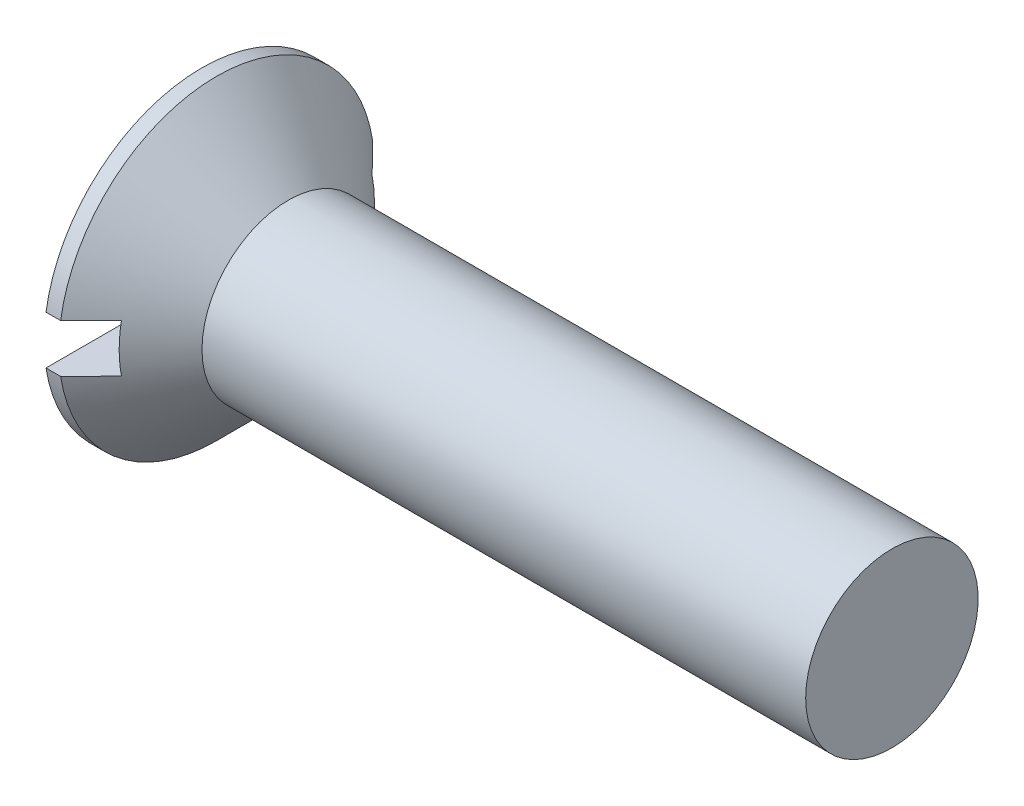
SolidWorks part; units mm, degrees
revolve "Base-Revolve" add sketch "BodySke" angle 360 about L5
sketch "BodySke" plane through (0, 0, 0) normal (0, 0, 1) x (1, 0, 0)
  line L0 (0, 0) -> (0, 9.15)
  line L1 (0, 9.15) -> (0.85, 9.15)
  line L2 (5, 5) -> (40, 5)
  line L3 (40, 5) -> (40, 0)
  line L4 (40, 0) -> (0, 0)
  line L5 (-6.35, 0) -> (82.55, 0) construction
  line L6 (5, -5) -> (40, -5) construction
  line L7 (0.85, -9.15) -> (5, -5) construction
  line L8 (0.85, 9.15) -> (5, 5)
  line L9 (0, -9.15) -> (0.85, -9.15) construction
  line L10 (6.5, 6.5875) -> (6.5, -2.9375) construction
  line L11 (5, 6.35) -> (5, -3.175) construction
  dimension "Head_ang" = 90
cosmetic thread "ThreadCosmetic" [suppressed] parameters "Thread_length"=2.8, "Thread_minor"=8.344
extrude "Slot" cut sketch "Sketch2" against normal blind 2.6
sketch "Sketch2" plane through (0, 0, 0) normal (-1, 0, 0) x (0, 0, 1)
  line L0 (-9.15, -1.4) -> (9.15, -1.4)
  line L1 (-9.15, -1.4) -> (-9.15, 1.4)
  line L2 (9.15, 1.4) -> (-9.15, 1.4)
  line L3 (9.15, 1.4) -> (9.15, -1.4)
  dimension "D1" = 0.5
  dimension "D2" = 5.5
  dimension "D3" = 2.75
ref_plane "Plane1" through (0, 0, 0) normal (0, 0, 1) x (1, 0, 0)
ref_plane "Plane2" through (0, 0, 0) normal (0, 1, 0) x (1, 0, 0)
ref_plane "Plane3" through (0, 0, 0) normal (1, 0, 0) x (0, 0, -1)
other "Configuration Table"
sketch "Sketch3" plane through (0, 0, 0) normal (-1, 0, 0) x (0, 0, 1)
  line L0 (-0.99, 4.94) -> (0.99, 4.94)
  line L1 (0.99, 4.94) -> (0.99, -4.94)
  line L2 (0.99, -4.94) -> (-0.99, -4.94)
  line L3 (-0.99, -4.94) -> (-0.99, 4.94)
  dimension "D1" = 1.55
  dimension "D2" = 0.395
ref_plane "Plane4" through (5.98, 0, 0) normal (-1, 0, 0) x (0, 0, 1)
sketch "Sketch4" plane through (5.98, 0, 0) normal (-1, 0, 0) x (0, 0, 1)
  line L0 (-0.495, 0.495) -> (0.495, 0.495)
  line L3 (0.495, 0.495) -> (0.495, -0.495)
  line L4 (0.495, -0.495) -> (-0.495, -0.495)
  line L5 (-0.495, -0.495) -> (-0.495, 0.495)
  dimension "D2" = 0.395
  dimension "D1" = 0.395
  dimension "D3" = 0.1975
  dimension "D4" = 0.1975
loft "Cross" cut profiles "Sketch3", "Sketch4"
pattern_circular "CirPattern1" count 2 every 90 about axis through (0, 0, 0) along (1, 0, 0) of "Cross"
sketch "ThdSchSke" plane through (0, 0, 0) normal (0, 0, 1) x (1, 0, 0)
  line L0 (6.5, -4.172) -> (5.9202, -5)
  line L1 (6.5, -4.172) -> (7.0798, -5)
  line L2 (7.0798, -5) -> (7.0798, -6.25)
  line L3 (-3.175, 0) -> (5.1513, 0) construction
  line L5 (7.0798, -6.25) -> (5.9202, -6.25)
  line L6 (5.9202, -6.25) -> (5.9202, -5)
  line L7 (0, 9.15) -> (0, 1.4) construction
  dimension "Thread_minor" = 2.439
  dimension "Diameter" = 3
  dimension "Start" = 2.2
revolve "ThreadSchematic" [suppressed] cut sketch "ThdSchSke" angle 360 about L3
pattern_linear "ThdSchPat" [suppressed]
equation "\"D1@Sketch3\" = \"Cross_dia@Sketch3\" / 2"
equation "\"D2@Sketch3\" = \"Cross_width@Sketch3\" / 2"
equation "\"D1@Sketch4\" = \"Cross_width@Sketch3\" *.5"
equation "\"D2@Sketch4\" = \"D1@Sketch4\""
equation "\"D4@Sketch4\" = \"D2@Sketch4\" / 2"
equation "\"D3@Sketch4\" = \"D1@Sketch4\" / 2"
equation "\"D1@Sketch2\" = \"Slot_width@Sketch2\" / 2"
equation "\"D2@Sketch2\" = \"Head_dia@BodySke\""
equation "\"D3@Sketch2\" = \"D2@Sketch2\" / 2"
equation "\"Thread_length@ThreadCosmetic\" = ((sgn( (\"Length@BodySke\" - \"Advance@BodySke\" - \"Head_ht@BodySke\" ) - \"Thread_nom@BodySke\" )-1)*( (\"Length@BodySke\" - \"Advance@BodySke\" - \"Head_ht@BodySke\" ) - \"Thread_nom@BodySke\" ))/-2+ \"Thread_nom@BodySke\""
equation "\"Thread_minor@ThdSchSke\" = \"Thread_minor@ThreadCosmetic\""
equation "\"Diameter@ThdSchSke\" = \"Diameter@BodySke\""
equation "\"Overcut@ThdSchSke\" = \"Diameter@BodySke\" * 1.25"
equation "\"Start@ThdSchSke\" = 0.000001 + \"Length@BodySke\" - \"Thread_length@ThreadCosmetic\"  '---Countersunk---"
equation "\"Num_threads@ThdSchPat\" = int( \"Thread_length@ThreadCosmetic\" / \"Advance@BodySke\" + 0.999 )  + 1"
equation "\"Advance@ThdSchPat\" = \"Thread_length@ThreadCosmetic\" /  (\"Num_threads@ThdSchPat\" - 1) 'relax it"
